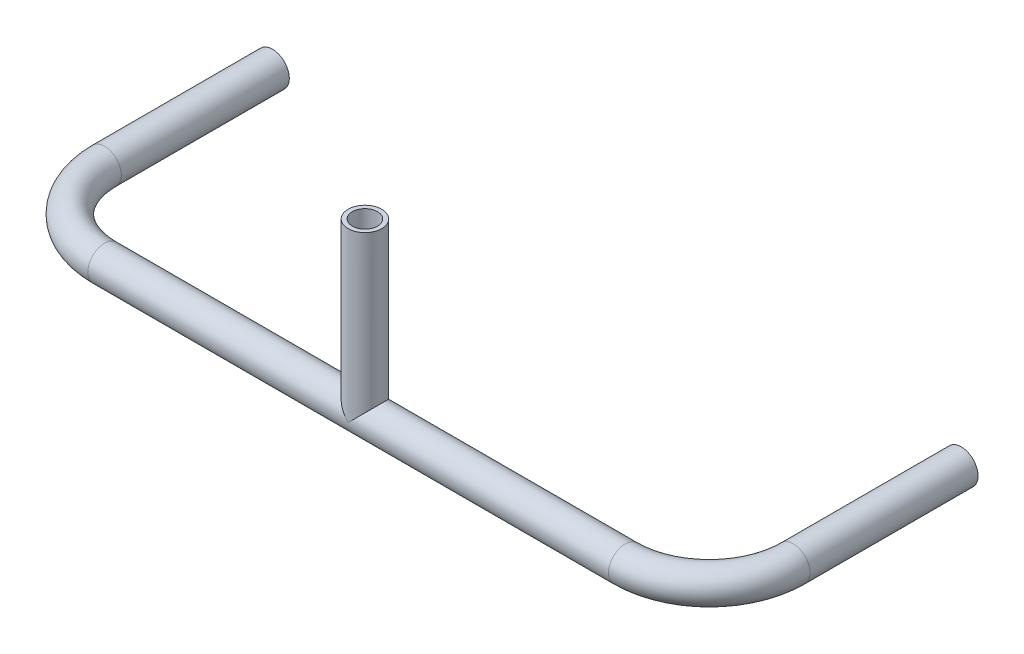
SolidWorks part; units mm, degrees
material "Copper"
ref_plane "Front Plane" through (0, 0, 0) normal (0, 0, 1) x (1, 0, 0)
ref_plane "Top Plane" through (0, 0, 0) normal (0, 1, 0) x (1, 0, 0)
ref_plane "Right Plane" through (0, 0, 0) normal (1, 0, 0) x (0, 0, -1)
sketch "Sketch2" plane through (0, 0, 0) normal (0, 1, 0) x (1, 0, 0)
  line L0 (0, 0) -> (-23597.9859, 0) construction
  line L1 (0, 0) -> (0, 23597.9859) construction
  line L2 (-41, 0) -> (-41, -20)
  line L3 (-31, -30) -> (31, -30)
  line L5 (41, -20) -> (41, 0)
  arc A0 (-41, -20) -> (-31, -30) centre (-31, -20) ccw
  arc A1 (41, -20) -> (31, -30) centre (31, -20) cw
  point P12 (0, 0)
  point P14 (0, -30)
  point P15 (0, 0)
  point P16 (0, 0)
  point P17 (0, 0)
  point P18 (0, 0)
  point P19 (0, 0)
  point P20 (0, 0)
  point P21 (-31.4344, -20.4344)
  point P22 (-30.6126, -19.6126)
  point P23 (0, 0)
  dimension "D3" = 10
  dimension "D1" = 82
  dimension "D2" = 30
  dimension "41" = 41
sketch "Sketch3" plane through (0, 0, 0) normal (0, 0, 1) x (1, 0, 0)
  line L0 (-31, 0) -> (-41, 0) construction
  line L1 (200000, 0) -> (-223597.9859, 0) construction
  circle A0 centre (-41, 0) radius 2
  circle A1 centre (-41, 0) radius 1.5
  point P6 (-43.4827, 0)
  dimension "D1" = 4
  dimension "D2" = 3
sweep "Sweep1" add profiles "Sketch3" path "Sketch2"
sketch "Sketch4" plane through (0, 0, 0) normal (0, 1, 0) x (1, 0, 0)
  line L0 (0, 0) -> (0, -50000) construction
  line L1 (0, 0) -> (-50000, 0) construction
  line L2 (-31, -30) -> (31, -30) construction
  circle A0 centre (0, -30) radius 2
  circle A1 centre (0, -30) radius 1.5
  dimension "D1" = 4
  dimension "3" = 3
extrude "Boss-Extrude1" add sketch "Sketch4" along normal blind 20
